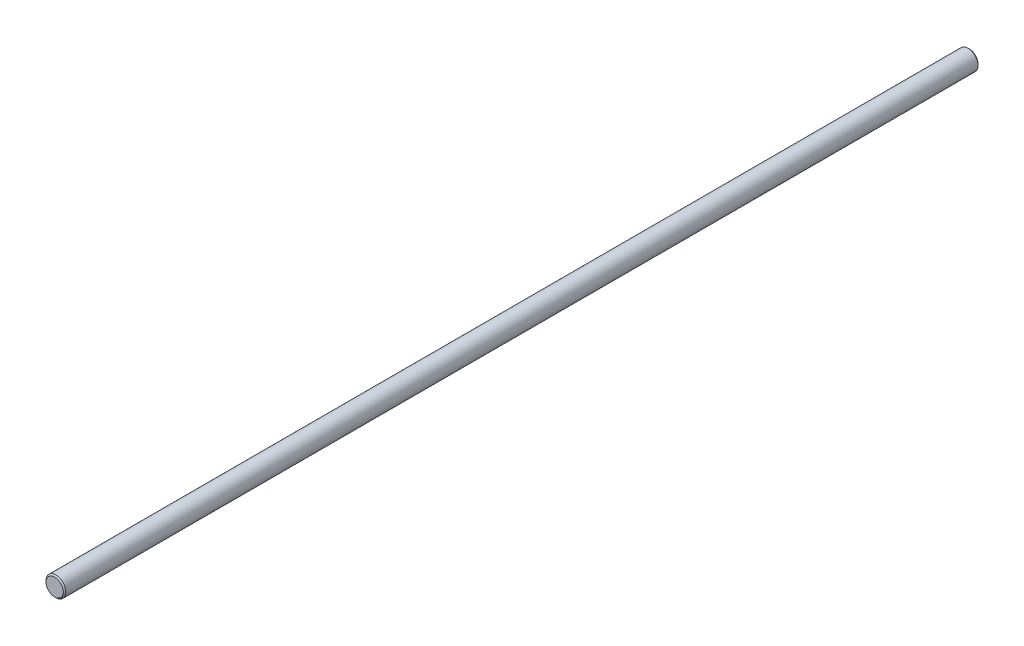
SolidWorks part; units mm, degrees
ref_plane "Front Plane" through (0, 0, 0) normal (0, 0, 1) x (1, 0, 0)
ref_plane "Top Plane" through (0, 0, 0) normal (0, 1, 0) x (1, 0, 0)
ref_plane "Right Plane" through (0, 0, 0) normal (1, 0, 0) x (0, 0, -1)
ref_plane "Plane1" through (0, 0, 0) normal (0, -1, 0) x (1, 0, 0)
sketch "Sketch1" plane through (0, 0, 0) normal (0, -1, 0) x (1, 0, 0)
  line L0 (3.5, 370) -> (0, 370)
  line L1 (0, 370) -> (0, 0)
  line L2 (0, 0) -> (3.5, 0)
  line L3 (3.5, 0) -> (4, 0.5)
  line L4 (4, 0.5) -> (4, 369.5)
  line L5 (4, 369.5) -> (3.5, 370)
  line L6 (0, 370) -> (0, 0) construction
  dimension "D1" = 3.5
  dimension "D2" = 0.7071
  dimension "D3" = 135
  dimension "D4" = 369
  dimension "D5" = 135
  dimension "D6" = 3.5
revolve "Revolve1" add sketch "Sketch1" angle 360 about L6
